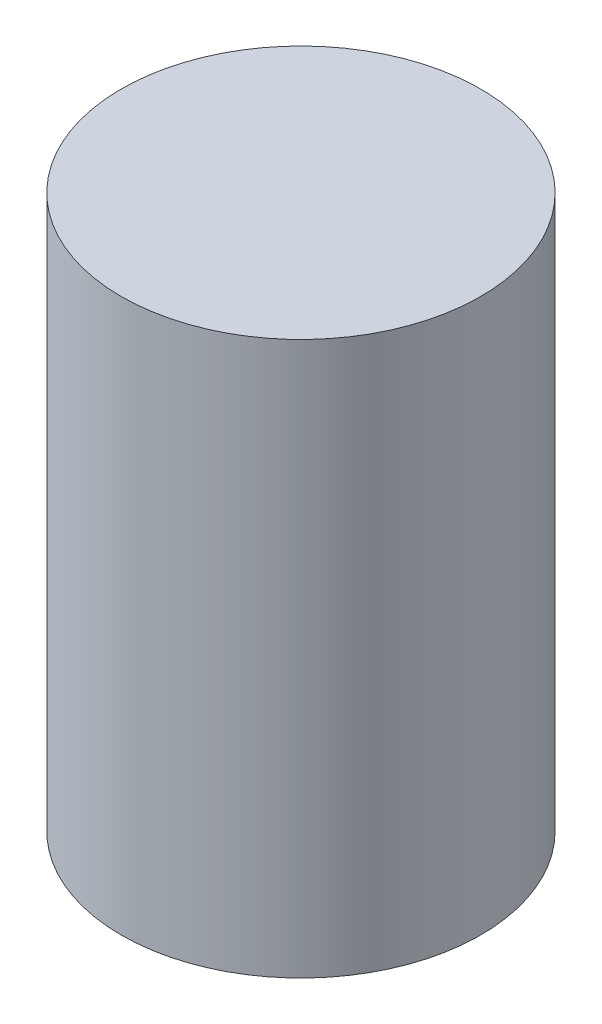
SolidWorks part; units mm, degrees
ref_plane "Front Plane" through (0, 0, 0) normal (0, 0, 1) x (1, 0, 0)
ref_plane "Top Plane" through (0, 0, 0) normal (0, 1, 0) x (1, 0, 0)
ref_plane "Right Plane" through (0, 0, 0) normal (1, 0, 0) x (0, 0, -1)
sketch "Sketch1" plane through (0, 0, 0) normal (0, 1, 0) x (1, 0, 0)
  circle A0 centre (0, 0) radius 1.3
  dimension "D1" = 2.6
extrude "Boss-Extrude1" add sketch "Sketch1" along normal blind 4
